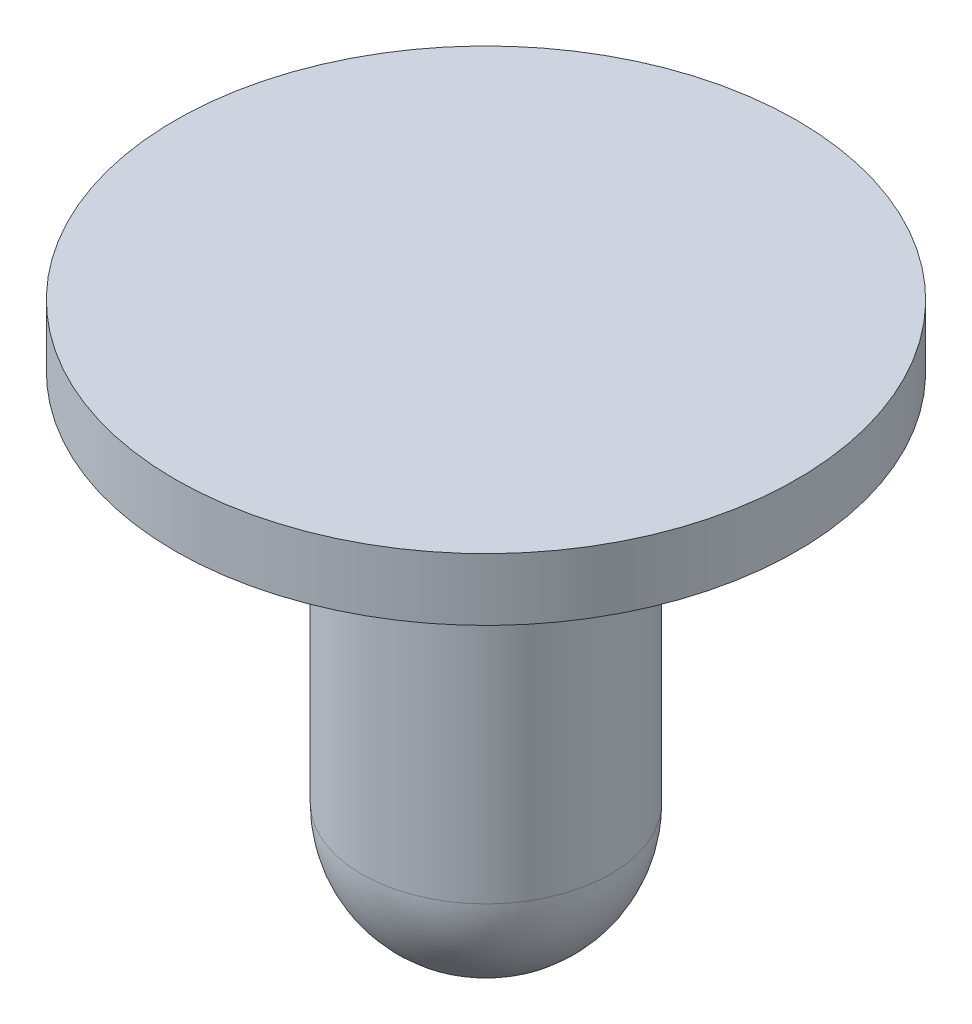
SolidWorks part; units mm, degrees
ref_plane "Front Plane" through (0, 0, 0) normal (0, 0, 1) x (1, 0, 0)
ref_plane "Top Plane" through (0, 0, 0) normal (0, 1, 0) x (1, 0, 0)
ref_plane "Right Plane" through (0, 0, 0) normal (1, 0, 0) x (0, 0, -1)
sketch "Sketch1" plane through (0, 0, 0) normal (0, 1, 0) x (1, 0, 0)
  circle A0 centre (0, 0) radius 12.7
  circle A1 centre (0, 0) radius 5.08
  dimension "D1" = 25.4
  dimension "D2" = 10.16
extrude "Boss-Extrude1" add sketch "Sketch1" along normal blind 2.54 contours A0
sketch "Sketch3" plane through (0, 0, 0) normal (0, -1, 0) x (1, 0, 0)
  circle A0 centre (0, 0) radius 5.08
  dimension "D1" = 10.16
extrude "Boss-Extrude2" add sketch "Sketch3" along normal blind 15.24
sketch "Sketch4" plane through (0, -15.24, 0) normal (0, -1, 0) x (1, 0, 0)
  line L0 (0, 5.08) -> (0, -5.08) construction
  circle A0 centre (0, 0) radius 5.08 construction
  circle A1 centre (0, 0) radius 5.08 construction
ref_plane "Plane1" through (0, 0, 0) normal (1, 0, 0) x (0, 0, -1)
sketch "Sketch5" plane through (0, 0, 0) normal (1, 0, 0) x (0, 0, -1)
  line L0 (0, -15.24) -> (0, -20.32) construction
  line L1 (0, -15.24) -> (0, -20.32)
  line L2 (-5.08, -15.24) -> (0, -15.24)
  arc A0 (-5.08, -15.24) -> (0, -20.32) centre (0, -15.24) ccw
  dimension "D1" = 5.08
  dimension "D2" = 5.08
  dimension "D3" = 20.32
revolve "Revolve2" add sketch "Sketch5" angle 360 about L0
